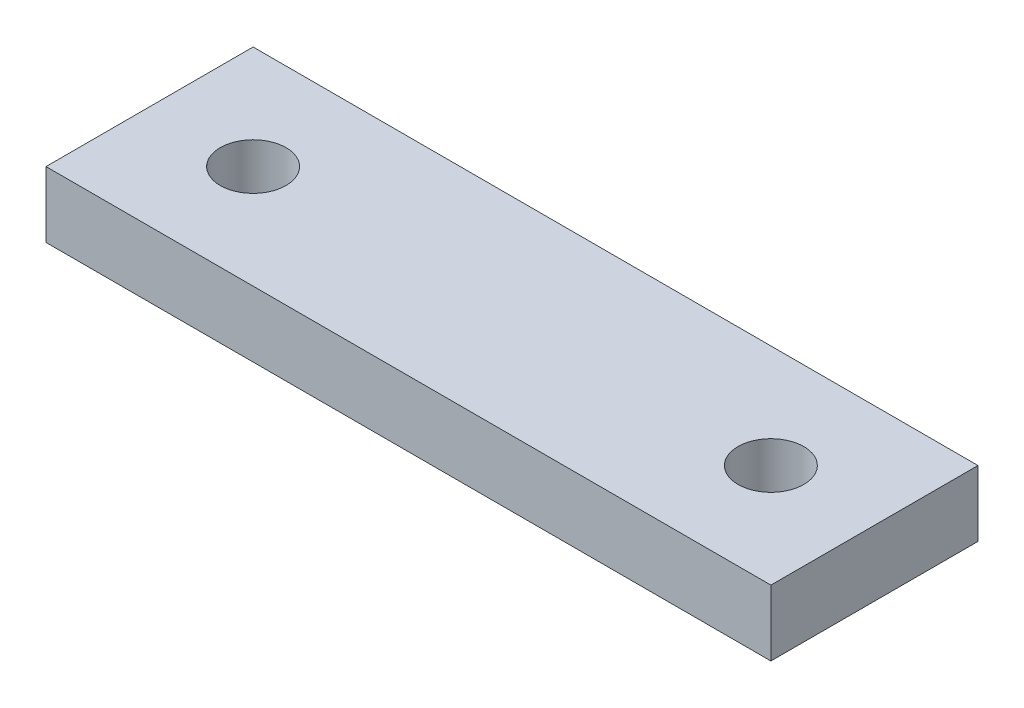
SolidWorks part; units mm, degrees
material "ABS"
ref_plane "Front Plane" through (0, 0, 0) normal (0, 0, 1) x (1, 0, 0)
ref_plane "Top Plane" through (0, 0, 0) normal (0, 1, 0) x (1, 0, 0)
ref_plane "Right Plane" through (0, 0, 0) normal (1, 0, 0) x (0, 0, -1)
sketch "Sketch1" plane through (0, 0, 0) normal (0, 1, 0) x (1, 0, 0)
  line L1 (-35, 10) -> (35, 10)
  line L2 (-35, 10) -> (-35, -10)
  line L3 (-35, -10) -> (35, -10)
  line L4 (35, 10) -> (35, -10)
  point P5 (0, 10)
  point P7 (-35, 0)
  dimension "D1" = 20
  dimension "D2" = 70
extrude "Boss-Extrude1" add sketch "Sketch1" along normal blind 6.35
sketch "Sketch2" plane through (0, 6.35, 0) normal (0, 1, 0) x (1, 0, 0)
  circle A0 centre (-25, 0) radius 3.175
  circle A1 centre (25, 0) radius 3.175
  dimension "D1" = 6.35
  dimension "D2" = 50
  dimension "D3" = 25
extrude "Cut-Extrude1" cut sketch "Sketch2" against normal up to surface (6.35 mm away) up to face at (0, 0, 0)
